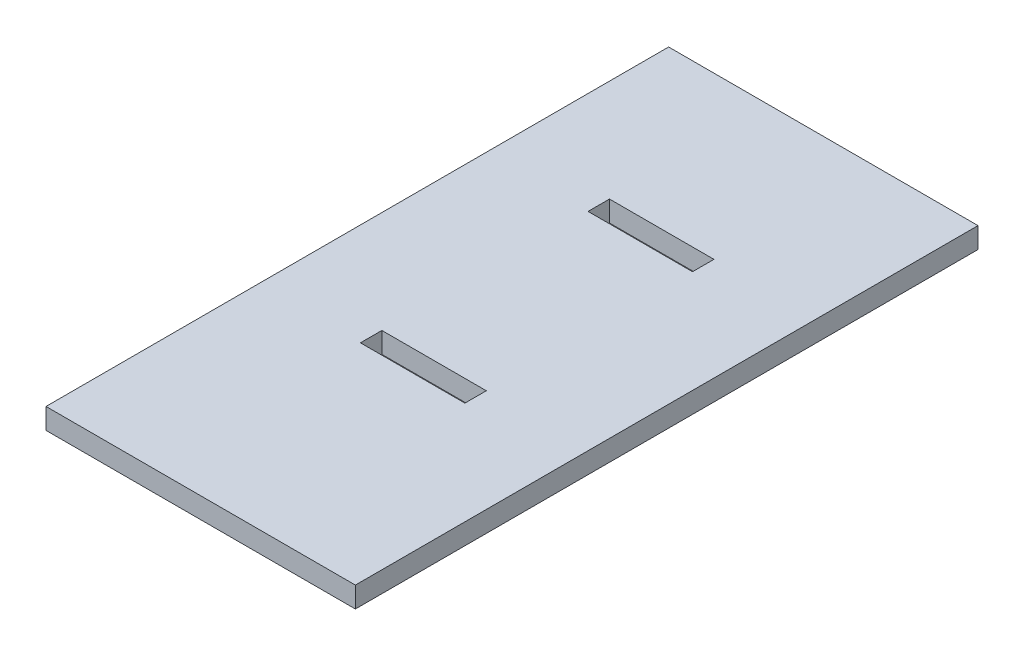
SolidWorks part; units mm, degrees
ref_plane "Front Plane" through (0, 0, 0) normal (0, 0, 1) x (1, 0, 0)
ref_plane "Top Plane" through (0, 0, 0) normal (0, 1, 0) x (1, 0, 0)
ref_plane "Right Plane" through (0, 0, 0) normal (1, 0, 0) x (0, 0, -1)
sketch "Sketch2" plane through (0, 0, 0) normal (0, 1, 0) x (1, 0, 0)
  line L0 (0, 45) -> (44.72, 45) construction
  line L29 (0, 0) -> (44.72, 0)
  line L30 (0, 0) -> (0, 90)
  line L47 (0, 90) -> (44.72, 90)
  line L65 (44.72, 0) -> (44.72, 90)
  line L66 (14.76, 33.79) -> (29.86, 33.79)
  line L67 (14.76, 33.79) -> (14.76, 30.69)
  line L68 (14.76, 30.69) -> (29.86, 30.69)
  line L69 (29.86, 33.79) -> (29.86, 30.69)
  line L75 (14.76, 66.69) -> (29.86, 66.69)
  line L76 (14.76, 66.69) -> (14.76, 63.59)
  line L77 (14.76, 63.59) -> (29.86, 63.59)
  line L78 (29.86, 66.69) -> (29.86, 63.59)
  dimension "D1" = 44.72
  dimension "D2" = 90
  dimension "D3" = 15.1
  dimension "D4" = 3.1
  dimension "D5" = 14.76
  dimension "D6" = 30.69
  dimension "D7" = 15.1
  dimension "D8" = 3.1
  dimension "D9" = 29.8
extrude "Boss-Extrude3" add sketch "Sketch2" along normal blind 3
